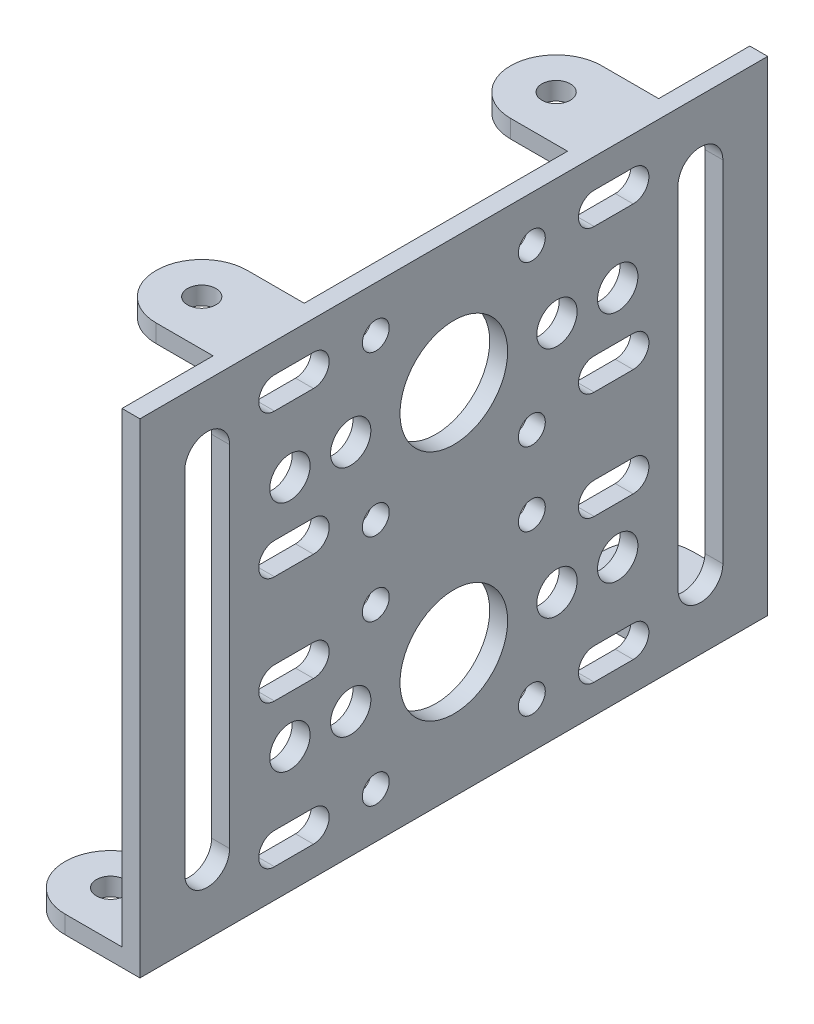
SolidWorks part; units mm, degrees
ref_plane "Front Plane" through (0, 0, 0) normal (0, 0, 1) x (1, 0, 0)
ref_plane "Top Plane" through (0, 0, 0) normal (0, 1, 0) x (1, 0, 0)
ref_plane "Right Plane" through (0, 0, 0) normal (1, 0, 0) x (0, 0, -1)
sketch "Sketch1" plane through (0, 0, 0) normal (1, 0, 0) x (0, 0, -1)
  line L0 (-18, 0) -> (18, 0)
  line L1 (0, 18) -> (0, -18)
  line L2 (88.0775, -1.458) -> (88.0775, 52.542)
  line L3 (53.0775, 52.542) -> (123.0775, 52.542)
  line L4 (53.0775, 52.542) -> (53.0775, -1.458)
  line L5 (53.0775, -1.458) -> (123.0775, -1.458)
  line L6 (123.0775, 52.542) -> (123.0775, -1.458)
  line L7 (60.5775, 47.542) -> (60.5775, 52.542)
  line L8 (58.0775, 25.542) -> (63.0775, 25.542)
  line L9 (58.0775, 6.042) -> (58.0775, 45.042)
  line L10 (113.0775, 6.042) -> (113.0775, 45.042)
  line L11 (63.0775, 6.042) -> (63.0775, 45.042)
  line L12 (118.0775, 6.042) -> (118.0775, 45.042)
  line L13 (53.0775, 25.542) -> (123.0775, 25.542)
  line L14 (118.0775, 25.542) -> (113.0775, 25.542)
  circle A0 centre (0, 0) radius 18
  circle A1 centre (7, 0) radius 6
  circle A2 centre (0, 16) radius 1.5
  circle A3 centre (0, -16) radius 1.5
  circle A4 centre (0, 0) radius 16
  circle A5 centre (13.5603, -8.4922) radius 1.5
  circle A6 centre (-13.5603, -8.4922) radius 1.5
  circle A7 centre (13.5603, 8.4922) radius 1.5
  circle A8 centre (-13.5603, 8.4922) radius 1.5
  circle A9 centre (69.8025, 13.3358) radius 2.25
  arc A10 (63.0775, 45.042) -> (58.0775, 45.042) centre (60.5775, 45.042) ccw
  circle A11 centre (106.3525, 13.3358) radius 2.25
  arc A12 (63.0775, 6.042) -> (58.0775, 6.042) centre (60.5775, 6.042) cw
  circle A13 centre (104.0775, 31.542) radius 1.5
  circle A14 centre (72.0775, 31.542) radius 1.5
  circle A15 centre (88.0775, 38.542) radius 6
  arc A16 (113.0775, 6.042) -> (118.0775, 6.042) centre (115.5775, 6.042) ccw
  circle A17 centre (106.3525, 37.7483) radius 2.25
  circle A18 centre (88.0775, 12.542) radius 6
  arc A19 (113.0775, 45.042) -> (118.0775, 45.042) centre (115.5775, 45.042) cw
  circle A20 centre (69.8025, 37.7483) radius 2.25
  circle A21 centre (72.0775, 19.542) radius 1.5
  circle A22 centre (104.0775, 19.542) radius 1.5
  dimension "D1" = 36
  dimension "D2" = 12
  dimension "D4" = 3
  dimension "D6" = 3
  dimension "D11" = 5
  dimension "D13" = 5
  dimension "D17" = 3
  dimension "D14" = 5
  dimension "D3" = 11
  dimension "D5" = 2
  dimension "D7" = 15.5
  dimension "D8" = 10.731
  dimension "D9" = 54
  dimension "D10" = 70
  dimension "D12" = 14
extrude "Boss-Extrude1" add sketch "Sketch1" along normal blind 2 contours A15 L2 L3 L7 A10 L11 L13 A14 A20 | L2 A18 L13 L11 A12 L9 L4 L5 A21 A9 | A10 L7 L3 L4 L13 L9 | L2 A18 L5 L6 L13 L12 A16 L10 A22 A11 | L10 A19 L12 L13 L6 L3 L2 A15 A17 A13
sketch "Sketch2" plane through (0, -1.458, 0) normal (0, -1, 0) x (1, 0, 0)
  line L0 (0, -88.0775) -> (2, -88.0775)
  line L1 (0, -53.0775) -> (2, -53.0775)
  line L2 (0, -53.0775) -> (0, -123.0775)
  line L3 (0, -123.0775) -> (2, -123.0775)
  line L4 (2, -53.0775) -> (2, -123.0775)
  line L5 (0, -53.0775) -> (-2.5, -53.0775)
  line L6 (0, -53.0775) -> (0, -58.0775)
  line L7 (0, -58.0775) -> (-2.5, -58.0775)
  line L8 (0, -58.0775) -> (0, -63.0775)
  line L9 (-2.5, -53.0775) -> (-2.5, -58.0775)
  line L10 (-5, -55.5775) -> (0, -55.5775)
  line L11 (0, -63.0775) -> (-2.5, -63.0775)
  line L12 (0, -63.0775) -> (0, -68.0775)
  line L13 (0, -68.0775) -> (-2.5, -68.0775)
  line L14 (-2.5, -63.0775) -> (-2.5, -68.0775)
  line L15 (-5, -65.5775) -> (0, -65.5775)
  line L16 (-5, -110.5775) -> (0, -110.5775)
  line L17 (-2.5, -113.0775) -> (-2.5, -108.0775)
  line L18 (0, -108.0775) -> (-2.5, -108.0775)
  line L19 (0, -113.0775) -> (0, -108.0775)
  line L20 (0, -113.0775) -> (-2.5, -113.0775)
  line L21 (-5, -120.5775) -> (0, -120.5775)
  line L22 (-2.5, -123.0775) -> (-2.5, -118.0775)
  line L23 (0, -118.0775) -> (0, -113.0775)
  line L24 (0, -118.0775) -> (-2.5, -118.0775)
  line L25 (0, -123.0775) -> (0, -118.0775)
  line L26 (0, -123.0775) -> (-2.5, -123.0775)
  line L28 (0, -53.0775) -> (2, -53.0775)
  line L29 (0, -53.0775) -> (0, -123.0775)
  line L30 (0, -123.0775) -> (2, -123.0775)
  line L31 (2, -53.0775) -> (2, -123.0775)
  circle A0 centre (-2.5, -55.5775) radius 1.5875
  arc A1 (-2.5, -53.0775) -> (-2.5, -58.0775) centre (-2.5, -55.5775) ccw
  circle A2 centre (-2.5, -65.5775) radius 1.5875
  arc A3 (-2.5, -63.0775) -> (-2.5, -68.0775) centre (-2.5, -65.5775) ccw
  arc A4 (-2.5, -113.0775) -> (-2.5, -108.0775) centre (-2.5, -110.5775) cw
  circle A5 centre (-2.5, -110.5775) radius 1.5875
  arc A6 (-2.5, -123.0775) -> (-2.5, -118.0775) centre (-2.5, -120.5775) cw
  circle A7 centre (-2.5, -120.5775) radius 1.5875
  line M1 (0, -53.0775) -> (0, -123.0775)
  dimension "D1" = 3.175
  dimension "D2" = 35
  dimension "D3" = 5
extrude "Boss-Extrude3" add sketch "Sketch2" against normal blind 2 contours L21 A7 L22 L26 L2 | L22 A7 L21 A6 | L21 A7 L22 A6 | L22 A7 L21 L2 L24 | L16 A5 L17 L20 L2 | L17 A5 L16 A4 | L16 A5 L17 A4 | L17 A5 L16 L2 L18 | A2 L14 L13 L12 L15 | A2 L15 L11 L14 M1 | L14 A3 L15 A2 | L15 A3 L14 A2 | L10 A1 L9 A0 | A0 L9 L7 L6 L10 | A0 L10 L5 L9 M1 | L9 A1 L10 A0
sketch "Sketch3" plane through (0, 0.542, 0) normal (0, 1, 0) x (1, 0, 0)
  line L1 (0, 113.0775) -> (-7.5213, 113.0775)
  line L2 (0, 113.0775) -> (0, 62.0203)
  line L3 (0, 62.0203) -> (-7.5213, 62.0203)
  line L4 (-7.5213, 113.0775) -> (-7.5213, 62.0203)
extrude "Cut-Extrude1" cut sketch "Sketch3" against normal blind 10
sketch "Sketch4" plane through (0, 52.542, 0) normal (0, 1, 0) x (1, 0, 0)
  line L0 (0, 123.0775) -> (0, 113.0775)
  line L1 (0, 53.0775) -> (0, 123.0775) construction
  line L2 (2, 88.0775) -> (0, 88.0775)
  line L3 (2, 53.0775) -> (2, 123.0775) construction
  line L4 (0, 68.0775) -> (-2.5, 68.0775)
  line L5 (0, 113.0775) -> (-2.5, 113.0775)
  line L6 (0, 113.0775) -> (0, 108.0775)
  line L7 (0, 108.0775) -> (-2.5, 108.0775)
  line L8 (0, 63.0775) -> (0, 68.0775)
  line L9 (0, 63.0775) -> (-2.5, 63.0775)
  arc A0 (-2.5, 113.0775) -> (-2.5, 108.0775) centre (-2.5, 110.5775) ccw
  circle A1 centre (-2.5, 110.5775) radius 1.5875
  circle A2 centre (-2.5, 65.5775) radius 1.5875
  arc A3 (-2.5, 63.0775) -> (-2.5, 68.0775) centre (-2.5, 65.5775) cw
  line M1 (0, 123.0775) -> (0, 53.0775)
  dimension "D1" = 3.175
extrude "Boss-Extrude4" add sketch "Sketch4" against normal blind 2 contours L5 A0 L7 A1 M1 | A3 L9 L4 A2 M1
sketch "Sketch5" plane through (2, 0, 0) normal (1, 0, 0) x (0, 0, -1)
  line L0 (110.9275, 22.082) -> (108.4275, 22.082)
  line L1 (65.2275, 22.082) -> (110.9275, 22.082)
  line L2 (65.2275, 22.082) -> (65.2275, 3.282)
  line L3 (65.2275, 3.282) -> (110.9275, 3.282)
  line L4 (110.9275, 22.082) -> (110.9275, 3.282)
  line L5 (108.4275, 22.082) -> (108.4275, 19.542)
  line L6 (88.0775, 22.082) -> (88.0775, 18.231)
  line L7 (72.0775, 19.542) -> (67.7275, 19.542)
  line L8 (69.9025, 19.542) -> (69.9025, 20.0633)
  line L9 (53.0775, 25.542) -> (60.1702, 25.542)
  line L10 (53.0775, 52.542) -> (53.0775, -1.458) construction
  line L11 (69.9025, 31.542) -> (69.9025, 31.0207)
  line L12 (72.0775, 31.542) -> (67.7275, 31.542)
  line L13 (88.0775, 29.002) -> (88.0775, 32.853)
  line L14 (108.4275, 29.002) -> (108.4275, 31.542)
  line L15 (110.9275, 29.002) -> (110.9275, 47.802)
  line L16 (65.2275, 47.802) -> (110.9275, 47.802)
  line L17 (65.2275, 29.002) -> (65.2275, 47.802)
  line L18 (65.2275, 29.002) -> (110.9275, 29.002)
  line L19 (110.9275, 29.002) -> (108.4275, 29.002)
  circle A0 centre (108.4275, 19.542) radius 1.55
  circle A1 centre (67.7275, 19.542) radius 1.55
  circle A2 centre (67.7275, 5.822) radius 1.55
  circle A3 centre (108.4275, 5.822) radius 1.55
  circle A4 centre (72.0775, 19.542) radius 1.55
  circle A5 centre (104.0775, 19.542) radius 1.55
  circle A6 centre (104.0775, 31.542) radius 1.55
  circle A7 centre (72.0775, 31.542) radius 1.55
  circle A8 centre (108.4275, 45.262) radius 1.55
  circle A9 centre (67.7275, 45.262) radius 1.55
  circle A10 centre (67.7275, 31.542) radius 1.55
  circle A11 centre (108.4275, 31.542) radius 1.55
  dimension "D4" = 3.1
  dimension "D1" = 45.7
  dimension "D2" = 18.8
  dimension "D3" = 2.5
extrude "Cut-Extrude2" cut sketch "Sketch5" against normal blind 2
sketch "Sketch7" plane through (0, 0.542, 0) normal (0, 1, 0) x (1, 0, 0)
  line L0 (0, 53.0775) -> (0, 63.2375)
  line L1 (0, 53.0775) -> (-2.5, 53.0775) construction
  line L2 (0, 53.0775) -> (0, 63.0775) construction
  line L3 (0, 58.1575) -> (-6.35, 58.1575)
  line L4 (0, 63.2375) -> (-6.35, 63.2375)
  line L5 (0, 53.0775) -> (-6.35, 53.0775)
  line L6 (0, 88.0775) -> (-33.5825, 88.0775)
  line L7 (0, 68.0775) -> (0, 108.0775) construction
  line L8 (0, 123.0775) -> (-6.35, 123.0775)
  line L9 (0, 112.9175) -> (-6.35, 112.9175)
  line L10 (0, 117.9975) -> (-6.35, 117.9975)
  line L11 (0, 123.0775) -> (0, 112.9175)
  arc A0 (-6.35, 63.2375) -> (-6.35, 53.0775) centre (-6.35, 58.1575) ccw
  circle A1 centre (-6.35, 58.1575) radius 1.5875
  circle A2 centre (-6.35, 117.9975) radius 1.5875
  arc A3 (-6.35, 112.9175) -> (-6.35, 123.0775) centre (-6.35, 117.9975) cw
  dimension "D2" = 3.175
  dimension "D1" = 10.16
extrude "Boss-Extrude6" add sketch "Sketch7" against normal blind 2
sketch "Sketch8" plane through (0, 52.542, 0) normal (0, 1, 0) x (1, 0, 0)
  line L1 (0, 113.0775) -> (-8.5563, 113.0775)
  line L2 (0, 113.0775) -> (0, 61.2213)
  line L3 (0, 61.2213) -> (-8.5563, 61.2213)
  line L4 (-8.5563, 113.0775) -> (-8.5563, 61.2213)
extrude "Cut-Extrude3" cut sketch "Sketch8" against normal blind 2
sketch "Sketch9" plane through (0, 52.542, 0) normal (0, 1, 0) x (1, 0, 0)
  line L0 (0, 123.0775) -> (0, 112.9175)
  line L1 (0, 112.9175) -> (0, 102.7575)
  line L2 (0, 53.0775) -> (0, 123.0775) construction
  line L3 (0, 88.0775) -> (2, 88.0775)
  line L4 (2, 53.0775) -> (2, 123.0775) construction
  line L5 (0, 107.8375) -> (-6.35, 107.8375)
  line L6 (-10.16, 64.9574) -> (-10.16, 71.6776)
  line L7 (0, 112.9175) -> (-6.35, 112.9175)
  line L8 (0, 112.9175) -> (0, 102.7575)
  line L9 (0, 102.7575) -> (-6.35, 102.7575)
  line L10 (-10.16, 111.1976) -> (-10.16, 104.4774)
  line L11 (0, 73.3975) -> (-6.35, 73.3975)
  line L12 (0, 63.2375) -> (0, 73.3975)
  line L13 (0, 63.2375) -> (-6.35, 63.2375)
  line L14 (0, 68.3175) -> (-6.35, 68.3175)
  line L15 (0, 63.2375) -> (0, 73.3975)
  arc A0 (-6.35, 112.9175) -> (-6.35, 102.7575) centre (-6.35, 107.8375) ccw
  circle A1 centre (-6.35, 107.8375) radius 1.5875
  circle A2 centre (-6.35, 68.3175) radius 1.5875
  arc A3 (-6.35, 63.2375) -> (-6.35, 73.3975) centre (-6.35, 68.3175) cw
  dimension "D3" = 3.175
  dimension "D1" = 10.16
  dimension "D2" = 6.35
extrude "Boss-Extrude31" add sketch "Sketch9" against normal blind 2
sketch "Sketch10" plane through (2, 0, 0) normal (1, 0, 0) x (0, 0, -1)
  line L0 (88.0775, 12.542) -> (88.0775, 18.542)
  line L2 (88.0775, 38.542) -> (88.0775, 32.542)
  line L4 (53.0775, 25.542) -> (68.2502, 25.542)
  line L5 (53.0775, 52.542) -> (53.0775, -1.458) construction
  circle A0 centre (88.0775, 12.542) radius 6 construction
  circle A1 centre (76.5775, 12.542) radius 2.25
  circle A2 centre (96.7775, 21.442) radius 1.5
  circle A3 centre (96.7775, 3.642) radius 1.5
  circle A4 centre (79.3775, 3.642) radius 1.5
  circle A5 centre (79.3775, 21.442) radius 1.5
  circle A6 centre (99.5775, 12.542) radius 2.25
  circle A7 centre (76.5775, 12.542) radius 2.25
  circle A8 centre (96.7775, 21.442) radius 1.5
  circle A9 centre (96.7775, 3.642) radius 1.5
  circle A10 centre (79.3775, 3.642) radius 1.5
  circle A11 centre (79.3775, 21.442) radius 1.5
  circle A12 centre (99.5775, 12.542) radius 2.25
  circle A13 centre (76.5775, 12.542) radius 2.25
  circle A14 centre (96.7775, 21.442) radius 1.5
  circle A15 centre (96.7775, 3.642) radius 1.5
  circle A16 centre (79.3775, 3.642) radius 1.5
  circle A17 centre (79.3775, 21.442) radius 1.5
  circle A18 centre (99.5775, 12.542) radius 2.25
  circle A19 centre (76.5775, 12.542) radius 2.25
  circle A20 centre (96.7775, 21.442) radius 1.5
  circle A21 centre (96.7775, 3.642) radius 1.5
  circle A22 centre (79.3775, 3.642) radius 1.5
  circle A23 centre (79.3775, 21.442) radius 1.5
  circle A24 centre (99.5775, 12.542) radius 2.25
  circle A25 centre (99.5775, 38.542) radius 2.25
  circle A26 centre (79.3775, 29.642) radius 1.5
  circle A27 centre (79.3775, 47.442) radius 1.5
  circle A28 centre (96.7775, 47.442) radius 1.5
  circle A29 centre (96.7775, 29.642) radius 1.5
  circle A30 centre (76.5775, 38.542) radius 2.25
  circle A31 centre (99.5775, 38.542) radius 2.25
  circle A32 centre (79.3775, 29.642) radius 1.5
  circle A33 centre (79.3775, 47.442) radius 1.5
  circle A34 centre (96.7775, 47.442) radius 1.5
  circle A35 centre (96.7775, 29.642) radius 1.5
  circle A36 centre (76.5775, 38.542) radius 2.25
  circle A37 centre (99.5775, 38.542) radius 2.25
  circle A38 centre (79.3775, 29.642) radius 1.5
  circle A39 centre (79.3775, 47.442) radius 1.5
  circle A40 centre (96.7775, 47.442) radius 1.5
  circle A41 centre (96.7775, 29.642) radius 1.5
  circle A42 centre (76.5775, 38.542) radius 2.25
  circle A43 centre (99.5775, 38.542) radius 2.25
  circle A44 centre (79.3775, 29.642) radius 1.5
  circle A45 centre (79.3775, 47.442) radius 1.5
  circle A46 centre (96.7775, 47.442) radius 1.5
  circle A47 centre (96.7775, 29.642) radius 1.5
  circle A48 centre (76.5775, 38.542) radius 2.25
  dimension "D3" = 4.5
  dimension "D7" = 3
extrude "Cut-Extrude4" cut sketch "Sketch10" against normal blind 10 contours A27 | A30 | A28 | A25 | A29 | A26 | A5 | A2 | A6 | A1 | A4 | A3
sketch "Sketch11" plane through (2, 0, 0) normal (1, 0, 0) x (0, 0, -1)
  line L0 (99.5775, 12.542) -> (106.3525, 12.542)
  circle A0 centre (69.8025, 37.7483) radius 2.25
  circle A1 centre (69.8025, 13.3358) radius 2.25
  circle A2 centre (106.3525, 37.7483) radius 2.25
  circle A3 centre (106.3525, 13.3358) radius 2.25
  dimension "D1" = 6.775
extrude "Boss-Extrude32" add sketch "Sketch11" against normal blind 2
sketch "Sketch12" plane through (2, 0, 0) normal (1, 0, 0) x (0, 0, -1)
  line L0 (76.5775, 12.542) -> (69.8025, 12.542)
  line L1 (53.0775, 25.542) -> (58.0775, 25.542)
  line L2 (53.0775, 52.542) -> (53.0775, -1.458) construction
  line L3 (58.0775, 6.042) -> (58.0775, 45.042) construction
  line L4 (88.0775, 12.542) -> (88.0775, 18.542)
  circle A0 centre (69.8025, 12.542) radius 2.25
  circle A2 centre (88.0775, 12.542) radius 6 construction
  circle A3 centre (69.8025, 38.542) radius 2.25
  circle A4 centre (106.3525, 12.542) radius 2.25
  circle A5 centre (106.3525, 38.542) radius 2.25
  dimension "D1" = 4.5
  dimension "D2" = 6.775
extrude "Cut-Extrude5" cut sketch "Sketch12" against normal blind 2
sketch "Sketch13" plane through (2, 0, 0) normal (1, 0, 0) x (0, 0, -1)
  line L0 (103.7275, 17.792) -> (108.0775, 17.792)
  line L1 (108.0775, 21.292) -> (103.7275, 21.292)
  line L2 (72.4275, 5.292) -> (68.0775, 5.292)
  line L3 (68.0775, 1.792) -> (72.4275, 1.792)
  line L4 (88.0775, -1.458) -> (88.0775, 5.292)
  line L5 (88.0775, 1.042) -> (88.0775, 5.292)
  line L6 (65.5775, 22.042) -> (110.5775, 22.042)
  line L7 (65.5775, 22.042) -> (65.5775, 1.042)
  line L8 (65.5775, 1.042) -> (110.5775, 1.042)
  line L9 (110.5775, 22.042) -> (110.5775, 1.042)
  line L10 (53.0775, -1.458) -> (123.0775, -1.458) construction
  line L11 (108.0775, 1.792) -> (103.7275, 1.792)
  line L12 (53.0775, 25.542) -> (59.8407, 25.542)
  line L13 (68.0775, 21.292) -> (72.4275, 21.292)
  line L14 (72.4275, 17.792) -> (68.0775, 17.792)
  line L15 (53.0775, 52.542) -> (53.0775, -1.458) construction
  line L16 (103.7275, 5.292) -> (108.0775, 5.292)
  line L17 (66.3275, 19.542) -> (65.5775, 19.542)
  line L18 (109.8275, 19.542) -> (110.5775, 19.542)
  line L19 (68.0775, 21.292) -> (68.0775, 22.042)
  line L20 (68.0775, 1.792) -> (68.0775, 1.042)
  line L21 (103.7275, 45.792) -> (108.0775, 45.792)
  line L22 (72.4275, 33.292) -> (68.0775, 33.292)
  line L23 (68.0775, 29.792) -> (72.4275, 29.792)
  line L24 (108.0775, 49.292) -> (103.7275, 49.292)
  line L25 (68.0775, 49.292) -> (72.4275, 49.292)
  line L26 (72.4275, 45.792) -> (68.0775, 45.792)
  line L27 (108.0775, 29.792) -> (103.7275, 29.792)
  line L28 (103.7275, 33.292) -> (108.0775, 33.292)
  arc A0 (108.0775, 1.792) -> (108.0775, 5.292) centre (108.0775, 3.542) ccw
  arc A1 (103.7275, 1.792) -> (103.7275, 5.292) centre (103.7275, 3.542) cw
  arc A2 (103.7275, 21.292) -> (103.7275, 17.792) centre (103.7275, 19.542) ccw
  arc A3 (68.0775, 21.292) -> (68.0775, 17.792) centre (68.0775, 19.542) ccw
  arc A4 (72.4275, 21.292) -> (72.4275, 17.792) centre (72.4275, 19.542) cw
  arc A5 (72.4275, 1.792) -> (72.4275, 5.292) centre (72.4275, 3.542) ccw
  arc A6 (68.0775, 1.792) -> (68.0775, 5.292) centre (68.0775, 3.542) cw
  arc A7 (108.0775, 21.292) -> (108.0775, 17.792) centre (108.0775, 19.542) cw
  arc A8 (108.0775, 29.792) -> (108.0775, 33.292) centre (108.0775, 31.542) ccw
  arc A9 (68.0775, 49.292) -> (68.0775, 45.792) centre (68.0775, 47.542) ccw
  arc A10 (72.4275, 49.292) -> (72.4275, 45.792) centre (72.4275, 47.542) cw
  arc A11 (72.4275, 29.792) -> (72.4275, 33.292) centre (72.4275, 31.542) ccw
  arc A12 (68.0775, 29.792) -> (68.0775, 33.292) centre (68.0775, 31.542) cw
  arc A13 (103.7275, 29.792) -> (103.7275, 33.292) centre (103.7275, 31.542) cw
  arc A14 (103.7275, 49.292) -> (103.7275, 45.792) centre (103.7275, 47.542) ccw
  arc A15 (108.0775, 49.292) -> (108.0775, 45.792) centre (108.0775, 47.542) cw
  circle M9 centre (104.0775, 19.542) radius 1.55
  circle M10 centre (108.4275, 19.542) radius 1.55
  circle M13 centre (67.7275, 19.542) radius 1.55
  circle M14 centre (67.7275, 5.822) radius 1.55
  circle M29 centre (72.0775, 19.542) radius 1.55
  circle M31 centre (67.7275, 45.262) radius 1.55
  circle M32 centre (108.4275, 45.262) radius 1.55
  circle M34 centre (108.4275, 5.822) radius 1.55
  dimension "D6" = 3.5
  dimension "D1" = 21
  dimension "D2" = 45
extrude "Cut-Extrude6" cut sketch "Sketch13" against normal blind 2 contours A10 L25 A9 L26 M31 | A15 L24 A14 L21 M32 | A7 L1 A2 L0 M10 M9 | A4 L13 A3 L14 M13 M29 | A6 L3 A5 L2 M14 | A1 L11 A0 L16 M34
sketch "Sketch14" plane through (2, 0, 0) normal (1, 0, 0) x (0, 0, -1)
  line L0 (68.0775, 5.292) -> (69.184, 5.292)
  line L1 (88.0775, -1.458) -> (88.0775, 2.9161)
  line L2 (53.0775, -1.458) -> (123.0775, -1.458) construction
  line L3 (53.0775, 25.542) -> (55.5826, 25.542)
  line L4 (53.0775, 52.542) -> (53.0775, -1.458) construction
  line L5 (108.0775, 5.292) -> (106.9709, 5.292)
  line L6 (123.0775, 25.542) -> (120.5723, 25.542)
  line L7 (108.0775, 45.792) -> (106.9709, 45.792)
  line L8 (68.0775, 45.792) -> (69.184, 45.792)
  arc A0 (69.184, 5.292) -> (66.7189, 4.645) centre (67.7275, 5.822) ccw
  arc A1 (68.0775, 5.292) -> (66.7189, 4.645) centre (68.0775, 3.542) ccw
  arc A2 (109.1953, 20.8884) -> (109.1953, 18.1956) centre (108.4275, 19.542) cw
  arc A3 (66.9596, 20.8884) -> (66.9596, 18.1956) centre (68.0775, 19.542) ccw
  arc A4 (66.9596, 20.8884) -> (66.9596, 18.1956) centre (67.7275, 19.542) ccw
  arc A5 (109.1953, 20.8884) -> (109.1953, 18.1956) centre (108.0775, 19.542) cw
  arc A6 (108.0775, 5.292) -> (109.4361, 4.645) centre (108.0775, 3.542) cw
  arc A7 (106.9709, 5.292) -> (109.4361, 4.645) centre (108.4275, 5.822) cw
  arc A8 (106.9709, 45.792) -> (109.4361, 46.439) centre (108.4275, 45.262) ccw
  arc A9 (108.0775, 45.792) -> (109.4361, 46.439) centre (108.0775, 47.542) ccw
  arc A10 (109.1953, 30.1956) -> (109.1953, 32.8884) centre (108.0775, 31.542) ccw
  arc A11 (66.9596, 30.1956) -> (66.9596, 32.8884) centre (67.7275, 31.542) cw
  arc A12 (66.9596, 30.1956) -> (66.9596, 32.8884) centre (68.0775, 31.542) cw
  arc A13 (109.1953, 30.1956) -> (109.1953, 32.8884) centre (108.4275, 31.542) ccw
  arc A14 (68.0775, 45.792) -> (66.7189, 46.439) centre (68.0775, 47.542) cw
  arc A15 (69.184, 45.792) -> (66.7189, 46.439) centre (67.7275, 45.262) cw
extrude "Boss-Extrude33" add sketch "Sketch14" against normal blind 2 contours A1 L0 A0 | A7 L5 A6 | A3 A4 | A2 A5 | A11 A12 | A10 A13 | A15 L8 A14 | A9 L7 A8
sketch "Sketch15" plane through (2, 0, 0) normal (1, 0, 0) x (0, 0, -1)
  line L0 (68.0775, 21.292) -> (72.4275, 21.292)
  line L1 (88.0775, -1.458) -> (88.0775, 13.1533)
  line L2 (72.4275, 17.792) -> (68.0775, 17.792)
  line L3 (53.0775, -1.458) -> (123.0775, -1.458) construction
  line L4 (68.0775, 3.542) -> (68.0775, 19.542)
  line L5 (68.0775, 11.542) -> (69.6791, 11.542)
  line L6 (72.4275, 5.292) -> (68.0775, 5.292)
  line L7 (68.0775, 1.792) -> (72.4275, 1.792)
  line L8 (108.0775, 1.792) -> (103.7275, 1.792)
  line L9 (103.7275, 5.292) -> (108.0775, 5.292)
  line L10 (108.0775, 11.542) -> (106.4758, 11.542)
  line L11 (108.0775, 3.542) -> (108.0775, 19.542)
  line L12 (103.7275, 17.792) -> (108.0775, 17.792)
  line L13 (108.0775, 21.292) -> (103.7275, 21.292)
  line L14 (53.0775, 25.542) -> (56.1943, 25.542)
  line L15 (53.0775, 52.542) -> (53.0775, -1.458) construction
  line L16 (108.0775, 29.792) -> (103.7275, 29.792)
  line L17 (103.7275, 33.292) -> (108.0775, 33.292)
  line L18 (108.0775, 47.542) -> (108.0775, 31.542)
  line L19 (108.0775, 39.542) -> (106.4758, 39.542)
  line L20 (103.7275, 45.792) -> (108.0775, 45.792)
  line L21 (108.0775, 49.292) -> (103.7275, 49.292)
  line L22 (68.0775, 49.292) -> (72.4275, 49.292)
  line L23 (72.4275, 45.792) -> (68.0775, 45.792)
  line L24 (68.0775, 39.542) -> (69.6791, 39.542)
  line L25 (68.0775, 47.542) -> (68.0775, 31.542)
  line L26 (72.4275, 33.292) -> (68.0775, 33.292)
  line L27 (68.0775, 29.792) -> (72.4275, 29.792)
  arc A0 (68.0775, 21.292) -> (68.0775, 17.792) centre (68.0775, 19.542) ccw
  arc A1 (72.4275, 17.792) -> (72.4275, 21.292) centre (72.4275, 19.542) ccw
  arc A2 (68.0775, 5.292) -> (68.0775, 1.792) centre (68.0775, 3.542) ccw
  arc A3 (72.4275, 5.292) -> (72.4275, 1.792) centre (72.4275, 3.542) cw
  arc A4 (68.0775, 1.792) -> (68.0775, 5.292) centre (68.0775, 3.542) cw
  arc A5 (108.0775, 1.792) -> (108.0775, 5.292) centre (108.0775, 3.542) ccw
  arc A6 (103.7275, 5.292) -> (103.7275, 1.792) centre (103.7275, 3.542) ccw
  arc A7 (108.0775, 5.292) -> (108.0775, 1.792) centre (108.0775, 3.542) cw
  arc A8 (103.7275, 17.792) -> (103.7275, 21.292) centre (103.7275, 19.542) cw
  arc A9 (108.0775, 21.292) -> (108.0775, 17.792) centre (108.0775, 19.542) cw
  arc A10 (108.0775, 29.792) -> (108.0775, 33.292) centre (108.0775, 31.542) ccw
  arc A11 (103.7275, 33.292) -> (103.7275, 29.792) centre (103.7275, 31.542) ccw
  arc A12 (108.0775, 45.792) -> (108.0775, 49.292) centre (108.0775, 47.542) ccw
  arc A13 (103.7275, 45.792) -> (103.7275, 49.292) centre (103.7275, 47.542) cw
  arc A14 (108.0775, 49.292) -> (108.0775, 45.792) centre (108.0775, 47.542) cw
  arc A15 (68.0775, 49.292) -> (68.0775, 45.792) centre (68.0775, 47.542) ccw
  arc A16 (72.4275, 45.792) -> (72.4275, 49.292) centre (72.4275, 47.542) ccw
  arc A17 (68.0775, 45.792) -> (68.0775, 49.292) centre (68.0775, 47.542) cw
  arc A18 (72.4275, 33.292) -> (72.4275, 29.792) centre (72.4275, 31.542) cw
  arc A19 (68.0775, 29.792) -> (68.0775, 33.292) centre (68.0775, 31.542) cw
extrude "Cut-Extrude8" cut sketch "Sketch15" against normal blind 2
